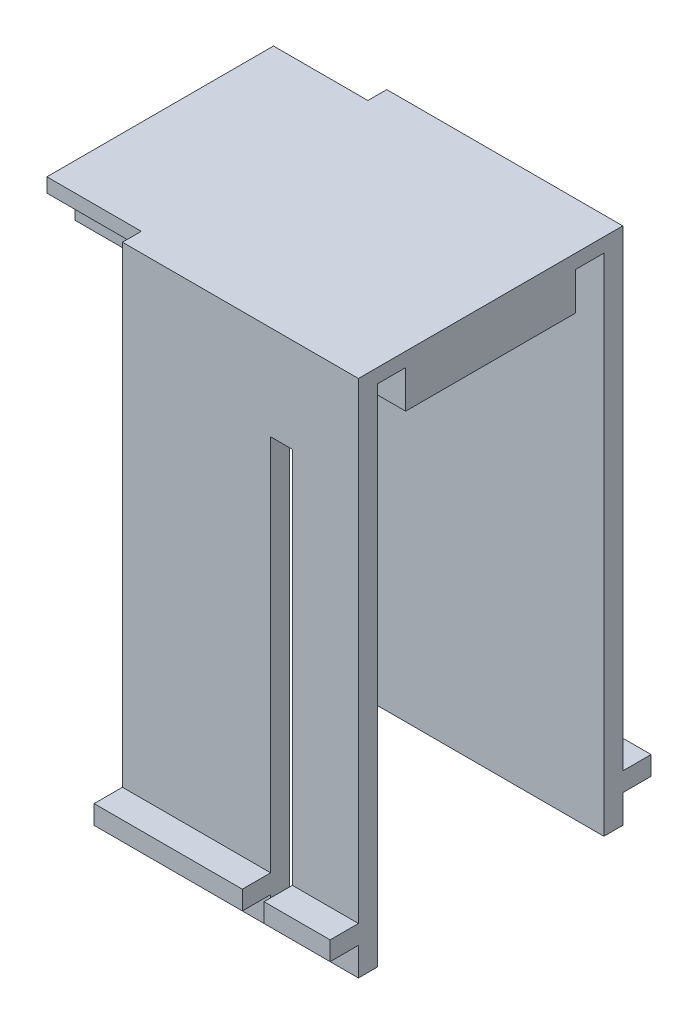
SolidWorks part; units mm, degrees
ref_plane "Front Plane" through (0, 0, 0) normal (0, 0, 1) x (1, 0, 0)
ref_plane "Top Plane" through (0, 0, 0) normal (0, 1, 0) x (1, 0, 0)
ref_plane "Right Plane" through (0, 0, 0) normal (1, 0, 0) x (0, 0, -1)
sketch "Sketch1" plane through (0, 0, 0) normal (0, 0, 1) x (1, 0, 0)
  line L1 (-12.5, 27.5) -> (12.5, 27.5)
  line L2 (-12.5, 27.5) -> (-12.5, -27.5)
  line L3 (-12.5, -27.5) -> (12.5, -27.5)
  line L4 (12.5, 27.5) -> (12.5, -27.5)
  line L5 (-12.5, 27.5) -> (12.5, -27.5) construction
  line L6 (-12.5, -27.5) -> (12.5, 27.5) construction
  point P0 (0, 0)
  dimension "D1" = 55
  dimension "D2" = 25
extrude "Boss-Extrude1" add sketch "Sketch1" along normal blind 2
sketch "Sketch2" plane through (0, 0, 0) normal (0, 0, -1) x (-1, 0, 0)
  line L1 (-12.5, 27.5) -> (22.5, 27.5)
  line L2 (-12.5, 27.5) -> (-12.5, 26)
  line L3 (-12.5, 26) -> (22.5, 26)
  line L4 (22.5, 27.5) -> (22.5, 26)
  dimension "D1" = 35
  dimension "D2" = 1.5
extrude "Boss-Extrude2" add sketch "Sketch2" along normal blind 24
sketch "Sketch3" plane through (0, 0, -24) normal (0, 0, -1) x (-1, 0, 0)
  line L1 (-12.5, 27.5) -> (12.5, 27.5)
  line L2 (-12.5, 27.5) -> (-12.5, -27.5)
  line L3 (-12.5, -27.5) -> (12.5, -27.5)
  line L4 (12.5, 27.5) -> (12.5, -27.5)
extrude "Boss-Extrude3" add sketch "Sketch3" along normal blind 2
sketch "Sketch4" plane through (0, 26, 0) normal (0, -1, 0) x (1, 0, 0)
  line L0 (-22.5, -24) -> (-22.5, 0) construction
  line L1 (-22.5, -3) -> (12.5, -3)
  line L2 (-22.5, -3) -> (-22.5, -21)
  line L3 (-22.5, -21) -> (12.5, -21)
  line L4 (12.5, -3) -> (12.5, -21)
  line L5 (12.5, -24) -> (12.5, 0) construction
  line L7 (12.5, -24) -> (-12.5, -24) construction
  line L8 (12.5, 0) -> (-12.5, 0) construction
  dimension "D1" = 3
  dimension "D2" = 3
extrude "Boss-Extrude4" add sketch "Sketch4" along normal blind 4
sketch "Sketch5" plane through (0, 0, 2) normal (0, 0, 1) x (1, 0, 0)
  line L0 (-12.5, -27.5) -> (12.5, -27.5) construction
  line L1 (5.5, -27.5) -> (3.2, -27.5)
  line L2 (5.5, -27.5) -> (5.5, 17.5)
  line L3 (5.5, 17.5) -> (3.2, 17.5)
  line L4 (3.2, -27.5) -> (3.2, 17.5)
  line L5 (12.5, -27.5) -> (12.5, 27.5) construction
  dimension "D1" = 2.3
  dimension "D2" = 7
  dimension "D3" = 45
extrude "Cut-Extrude1" cut sketch "Sketch5" against normal up to surface (2 mm away) up to face at (0, -0.75, 0)
sketch "Sketch6" plane through (0, 0, 2) normal (0, 0, 1) x (1, 0, 0)
  line L0 (-12.5, 27.5) -> (-12.5, -27.5) construction
  line L1 (-12.5, -22.5) -> (3.2, -22.5)
  line L2 (-12.5, -22.5) -> (-12.5, -24.5)
  line L3 (-12.5, -24.5) -> (3.2, -24.5)
  line L4 (3.2, -22.5) -> (3.2, -24.5)
  line L5 (3.2, 17.5) -> (3.2, -27.5) construction
  line L6 (5.5, -27.5) -> (5.5, 17.5) construction
  line L7 (5.5, -22.5) -> (12.5, -22.5)
  line L8 (5.5, -22.5) -> (5.5, -24.5)
  line L9 (5.5, -24.5) -> (12.5, -24.5)
  line L10 (12.5, -22.5) -> (12.5, -24.5)
  line L11 (12.5, -27.5) -> (12.5, 27.5) construction
  line L12 (5.5, -27.5) -> (12.5, -27.5) construction
  dimension "D1" = 3
  dimension "D2" = 2
extrude "Boss-Extrude5" add sketch "Sketch6" along normal blind 3
sketch "Sketch7" plane through (0, 0, -26) normal (0, 0, -1) x (-1, 0, 0)
  line L0 (-12.5, 27.5) -> (-12.5, -27.5) construction
  line L1 (-12.5, -22.5) -> (12.5, -22.5)
  line L2 (-12.5, -22.5) -> (-12.5, -24.5)
  line L3 (-12.5, -24.5) -> (12.5, -24.5)
  line L4 (12.5, -22.5) -> (12.5, -24.5)
  line L5 (12.5, -27.5) -> (12.5, 27.5) construction
  line L6 (-5.5, -24.5) -> (-12.5, -24.5) construction
  line L7 (-12.5, -22.5) -> (-5.5, -22.5) construction
extrude "Boss-Extrude6" add sketch "Sketch7" along normal blind 3
